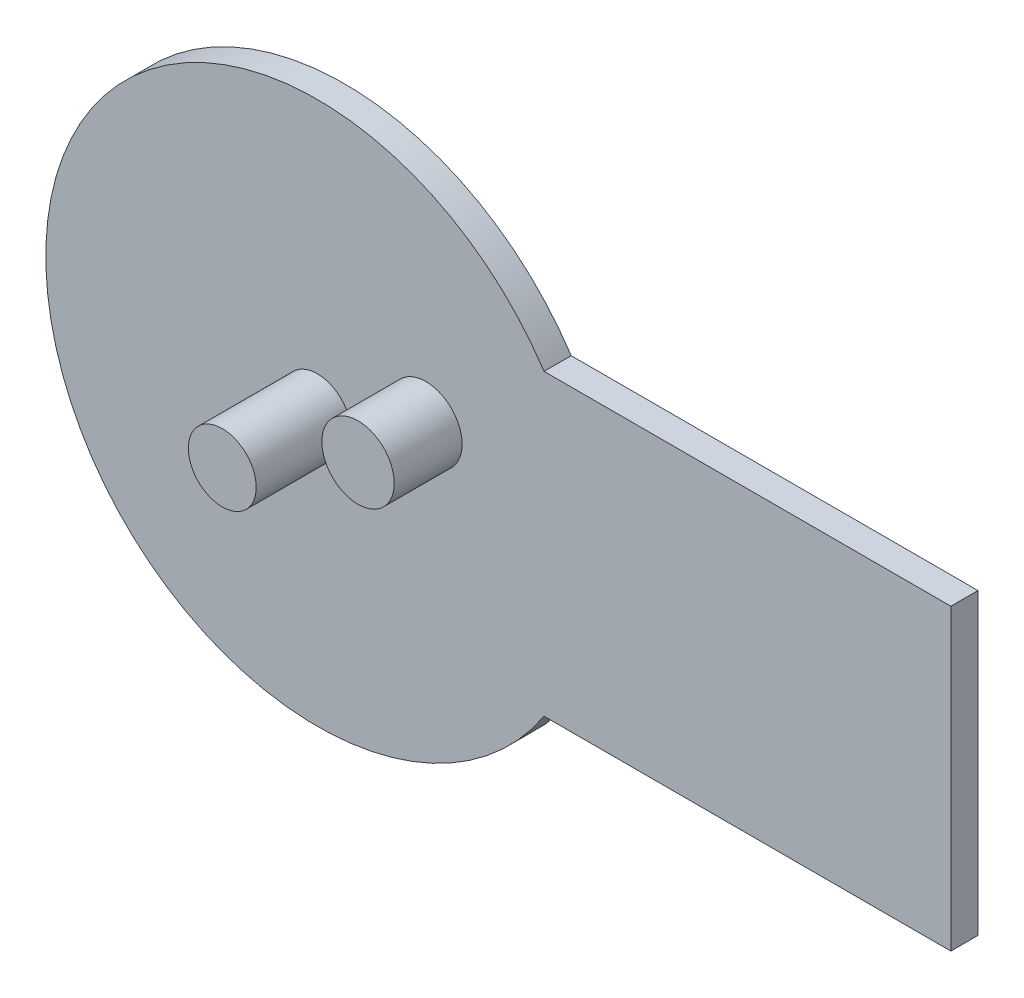
SolidWorks part; units mm, degrees
ref_plane "前视基准面" through (0, 0, 0) normal (0, 0, 1) x (1, 0, 0)
ref_plane "上视基准面" through (0, 0, 0) normal (0, 1, 0) x (1, 0, 0)
ref_plane "右视基准面" through (0, 0, 0) normal (1, 0, 0) x (0, 0, -1)
sketch "Sketch1" plane through (0, 0, 0) normal (0, 0, 1) x (1, 0, 0)
  circle A0 centre (0, 0) radius 30
extrude "Boss-Extrude1" add sketch "Sketch1" along normal blind 3
sketch "Sketch2" plane through (0, 0, 3) normal (0, 0, 1) x (1, 0, 0)
  circle A0 centre (0, 0) radius 3.75
  dimension "D1" = 7.5
extrude "Boss-Extrude2" add sketch "Sketch2" along normal blind 10.5
sketch "Sketch3" plane through (0, 0, 3) normal (0, 0, 1) x (1, 0, 0)
  circle A1 centre (12, 5) radius 4
  point P6 (0, 0)
  dimension "D1" = 5
  dimension "D2" = 12
extrude "Boss-Extrude3" add sketch "Sketch3" along normal blind 7.5
sketch "Sketch4" plane through (0, 0, 3) normal (0, 0, 1) x (1, 0, 0)
  line L0 (25.7688, 0) -> (75.3766, 0) construction
  line L1 (25.0549, 16.5) -> (70, 16.5)
  line L2 (25.0549, -16.5) -> (70, -16.5)
  line L3 (30, 0) -> (30, 16.5) construction
  line L4 (70, 16.5) -> (70, -16.5)
  circle A0 centre (0, 0) radius 30 construction
  arc A1 (25.0549, 16.5) -> (25.0549, -16.5) centre (0, 0) cw
  dimension "D1" = 16.5
  dimension "D2" = 40
extrude "Boss-Extrude4" add sketch "Sketch4" against normal blind 3
